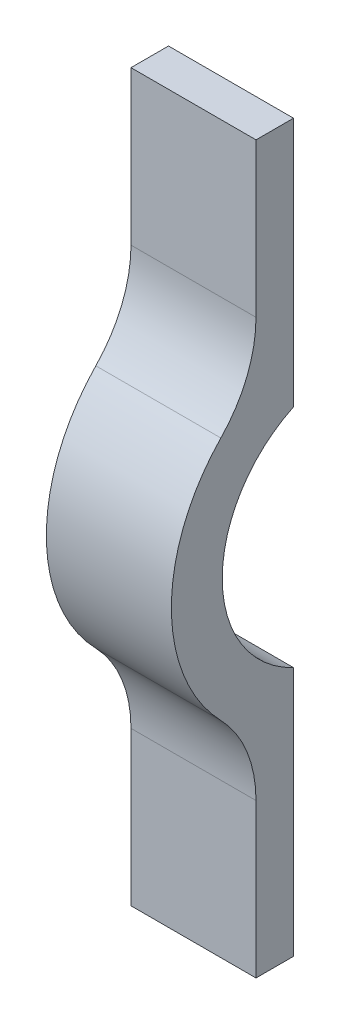
SolidWorks part; units mm, degrees
ref_plane "前视基准面" through (0, 0, 0) normal (0, 0, 1) x (1, 0, 0)
ref_plane "上视基准面" through (0, 0, 0) normal (0, 1, 0) x (1, 0, 0)
ref_plane "右视基准面" through (0, 0, 0) normal (1, 0, 0) x (0, 0, -1)
other "Configuration Table"
sketch "草图1" plane through (0, 0, 0) normal (1, 0, 0) x (0, 0, -1)
  line L4 (0, 0) -> (-4.3, 0) construction
  line L5 (-4.3, 0) -> (-4.3, 21.9644) construction
  line L6 (-10, 0) -> (-4.3, 0) construction
  line L7 (-4.3, 9.0283) -> (-4.3, 29.0283)
  line L8 (-4.3, 29.0283) -> (-7.3, 29.0283)
  line L9 (-7.3, 29.0283) -> (-7.3, 12.0283)
  line L10 (-14.0702, 0) -> (-10, 0)
  arc A2 (-10, 0) -> (-4.3, 9.0283) centre (0, 0) cw
  arc A3 (-7.3, 12.0283) -> (-14.0702, 0) centre (0, 0) ccw
  dimension "D1" = 10
  dimension "D2" = 3
  dimension "D3" = 20
  dimension "D4" = 17
  dimension "D5" = 4.3
extrude "凸台-拉伸1" add sketch "草图1" along normal blind 10
mirror "镜向1" about plane through (10, 0, 14.0702) normal (0, 1, 0) of "凸台-拉伸1"
fillet "圆角1" radius 10 2 edges at (5, -12.0283, 7.3) (5, 12.0283, 7.3)
